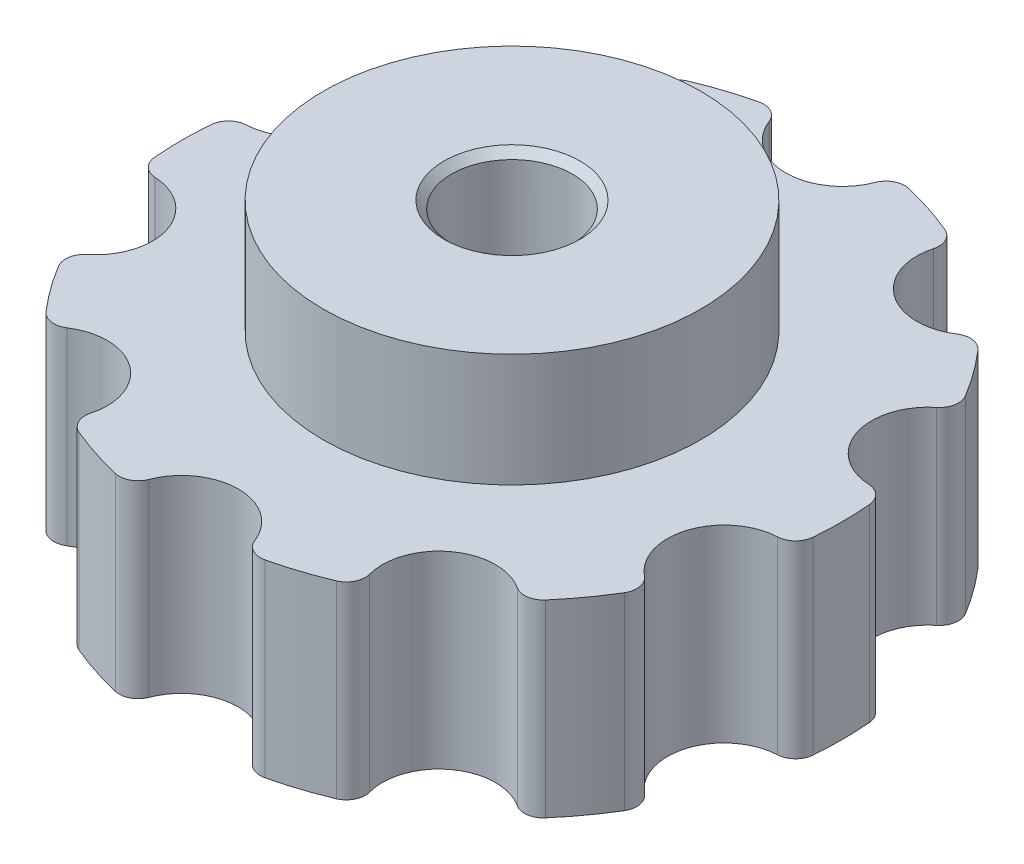
SolidWorks part; units mm, degrees
ref_plane "Front Plane" through (0, 0, 0) normal (0, 0, 1) x (1, 0, 0)
ref_plane "Top Plane" through (0, 0, 0) normal (0, 1, 0) x (1, 0, 0)
ref_plane "Right Plane" through (0, 0, 0) normal (1, 0, 0) x (0, 0, -1)
sketch "Sketch1" plane through (0, 0, 0) normal (0, 1, 0) x (1, 0, 0)
  circle A0 centre (0, 0) radius 8.75
  dimension "D1" = 17.5
extrude "Boss-Extrude1" add sketch "Sketch1" along normal blind 5
sketch "Sketch2" plane through (0, 5, 0) normal (0, 1, 0) x (1, 0, 0)
  line L0 (0, 0) -> (0, 8.75) construction
  line L1 (0, 0) -> (5.1431, 7.0789) construction
  circle A0 centre (0, 0) radius 8.75 construction
  circle A1 centre (0, 8.75) radius 1.5
  circle A2 centre (5.1431, 7.0789) radius 1.5
  circle A3 centre (8.3217, 2.7039) radius 1.5
  circle A4 centre (8.3217, -2.7039) radius 1.5
  circle A5 centre (5.1431, -7.0789) radius 1.5
  circle A6 centre (0, -8.75) radius 1.5
  circle A7 centre (-5.1431, -7.0789) radius 1.5
  circle A8 centre (-8.3217, -2.7039) radius 1.5
  circle A9 centre (-8.3217, 2.7039) radius 1.5
  circle A10 centre (-5.1431, 7.0789) radius 1.5
  point P28 (0, 0)
  dimension "D1" = 3
  dimension "D4" = 5.1431
  dimension "D3" = 36
  dimension "D2" = 10
extrude "Cut-Extrude1" cut sketch "Sketch2" against normal through all
fillet "Fillet1" radius 0.5 20 edges at (-6.2766, 2.5, -6.0964) (-3.8585, 2.5, -7.8533) (-8.6613, 2.5, -1.2428) (-7.7376, 2.5, -4.0855) (-7.7376, 2.5, 4.0855) (-8.6613, 2.5, 1.2428) (-3.8585, 2.5, 7.8533) (-6.2766, 2.5, 6.0964) (1.4945, 2.5, 8.6214) (-1.4945, 2.5, 8.6214) (6.2766, 2.5, 6.0964) (3.8585, 2.5, 7.8533) (8.6613, 2.5, 1.2428) (7.7376, 2.5, 4.0855) (7.7376, 2.5, -4.0855) (8.6613, 2.5, -1.2428) (3.8585, 2.5, -7.8533) (6.2766, 2.5, -6.0964) (-1.4945, 2.5, -8.6214) (1.4945, 2.5, -8.6214)
sketch "Sketch3" plane through (0, 5, 0) normal (0, 1, 0) x (1, 0, 0)
  circle A0 centre (0, 0) radius 5
  dimension "D1" = 10
extrude "Boss-Extrude2" add sketch "Sketch3" along normal blind 3
sketch "Sketch4" plane through (0, 0, 0) normal (0, -1, 0) x (1, 0, 0)
  line L0 (0, 0) -> (5, 0) construction
  line L1 (0, 0) -> (2.7496, 1.5875) construction
  line L2 (2.7496, 1.5875) -> (0, 3.175)
  line L3 (0, 3.175) -> (-2.7496, 1.5875)
  line L4 (-2.7496, 1.5875) -> (-2.7496, -1.5875)
  line L5 (-2.7496, -1.5875) -> (0, -3.175)
  line L6 (0, -3.175) -> (2.7496, -1.5875)
  line L7 (2.7496, -1.5875) -> (2.7496, 1.5875)
  circle A0 centre (0, 0) radius 3.175 construction
  dimension "D2" = 6.35
  dimension "D1" = 5
  dimension "D3" = 30
extrude "Cut-Extrude2" cut sketch "Sketch4" against normal blind 3
sketch "Sketch5" plane through (0, 8, 0) normal (0, 1, 0) x (1, 0, 0)
  circle A0 centre (0, 0) radius 1.6
  dimension "D1" = 3.2
extrude "Cut-Extrude3" cut sketch "Sketch5" against normal through all
chamfer "Chamfer1" distance 0.2 angle 45 1 edges at (0, 8, 1.6)
